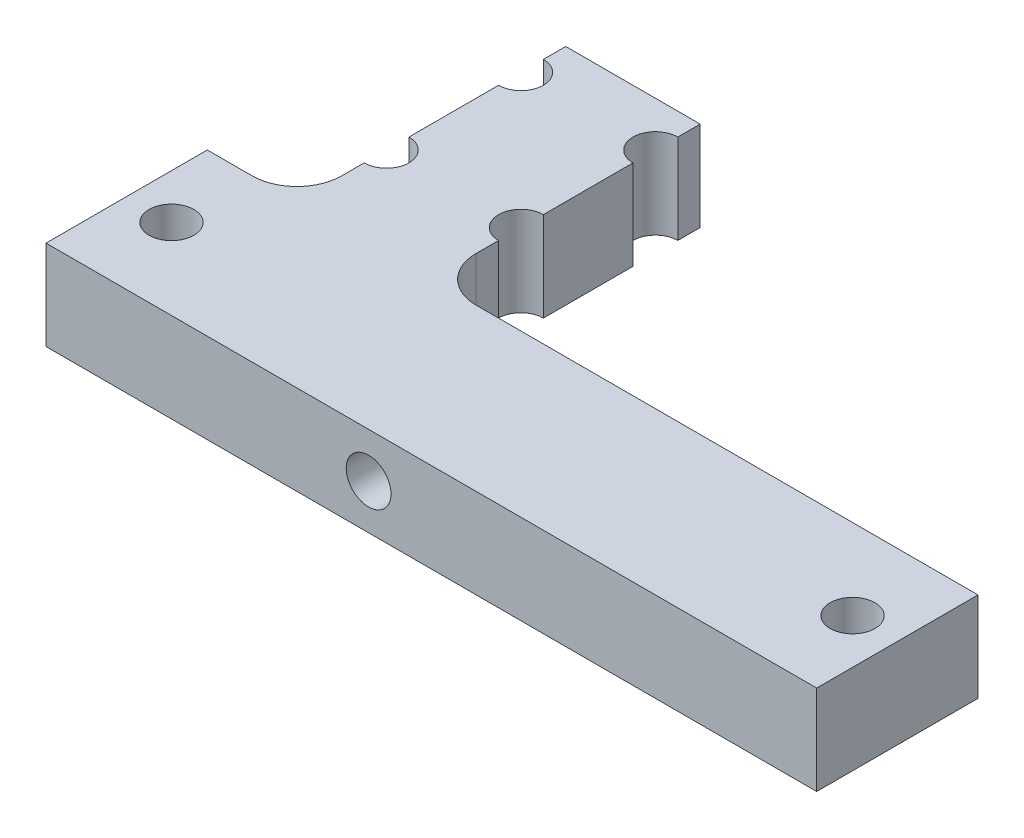
SolidWorks part; units mm, degrees
ref_plane "Front Plane" through (0, 0, 0) normal (0, 0, 1) x (1, 0, 0)
ref_plane "Top Plane" through (0, 0, 0) normal (0, 1, 0) x (1, 0, 0)
ref_plane "Right Plane" through (0, 0, 0) normal (1, 0, 0) x (0, 0, -1)
sketch "Sketch1" plane through (0, 0, 0) normal (0, 1, 0) x (1, 0, 0)
  line L0 (-27.305, 0) -> (27.305, 0) construction
  line L1 (-27.305, 5.715) -> (-20.955, 5.715)
  line L2 (-27.305, 5.715) -> (-27.305, -5.715)
  line L3 (-27.305, -5.715) -> (27.305, -5.715)
  line L4 (27.305, 5.715) -> (27.305, -5.715)
  line L5 (-27.305, 5.715) -> (27.305, -5.715) construction
  line L6 (-27.305, -5.715) -> (27.305, 5.715) construction
  line L7 (-20.955, 5.715) -> (-20.955, 10.4775)
  line L8 (-11.43, 5.715) -> (-11.43, 10.4775)
  line L9 (-20.955, 24.765) -> (-11.43, 24.765)
  line L10 (-11.43, 5.715) -> (27.305, 5.715)
  line L11 (-11.43, 23.1775) -> (-11.43, 24.765)
  line L12 (-11.43, 13.6525) -> (-11.43, 20.0025)
  line L13 (-20.955, 23.1775) -> (-20.955, 24.765)
  line L14 (-20.955, 13.6525) -> (-20.955, 20.0025)
  circle A0 centre (-24.13, 0) radius 1.5875
  circle A1 centre (24.13, 0) radius 1.5875
  arc A2 (-11.43, 23.1775) -> (-11.43, 20.0025) centre (-11.43, 21.59) ccw
  arc A3 (-11.43, 13.6525) -> (-11.43, 10.4775) centre (-11.43, 12.065) ccw
  arc A4 (-20.955, 20.0025) -> (-20.955, 23.1775) centre (-20.955, 21.59) ccw
  arc A5 (-20.955, 10.4775) -> (-20.955, 13.6525) centre (-20.955, 12.065) ccw
  point P0 (0, 0)
  dimension "D3" = 3.175
  dimension "D5" = 3.175
  dimension "D9" = 3.175
  dimension "D1" = 11.43
  dimension "D2" = 54.61
  dimension "D4" = 3.175
  dimension "D6" = 9.525
  dimension "D7" = 6.35
  dimension "D8" = 19.05
  dimension "D10" = 3.175
  dimension "D11" = 6.35
extrude "Boss-Extrude1" add sketch "Sketch1" along normal blind 6.35
fillet "Fillet1" radius 3.175 2 edges at (-20.955, 3.175, -5.715) (-11.43, 3.175, -5.715)
sketch "Sketch2" plane through (0, 0, -5.715) normal (0, 0, -1) x (-1, 0, 0)
  line L0 (-27.305, 6.35) -> (-27.305, 0) construction
  line L1 (-27.305, 3.175) -> (-0.5177, 3.175) construction
  circle A0 centre (4.445, 3.175) radius 1.5875
  dimension "D1" = 3.175
  dimension "D2" = 31.75
extrude "ties hole" cut sketch "Sketch2" against normal through all
